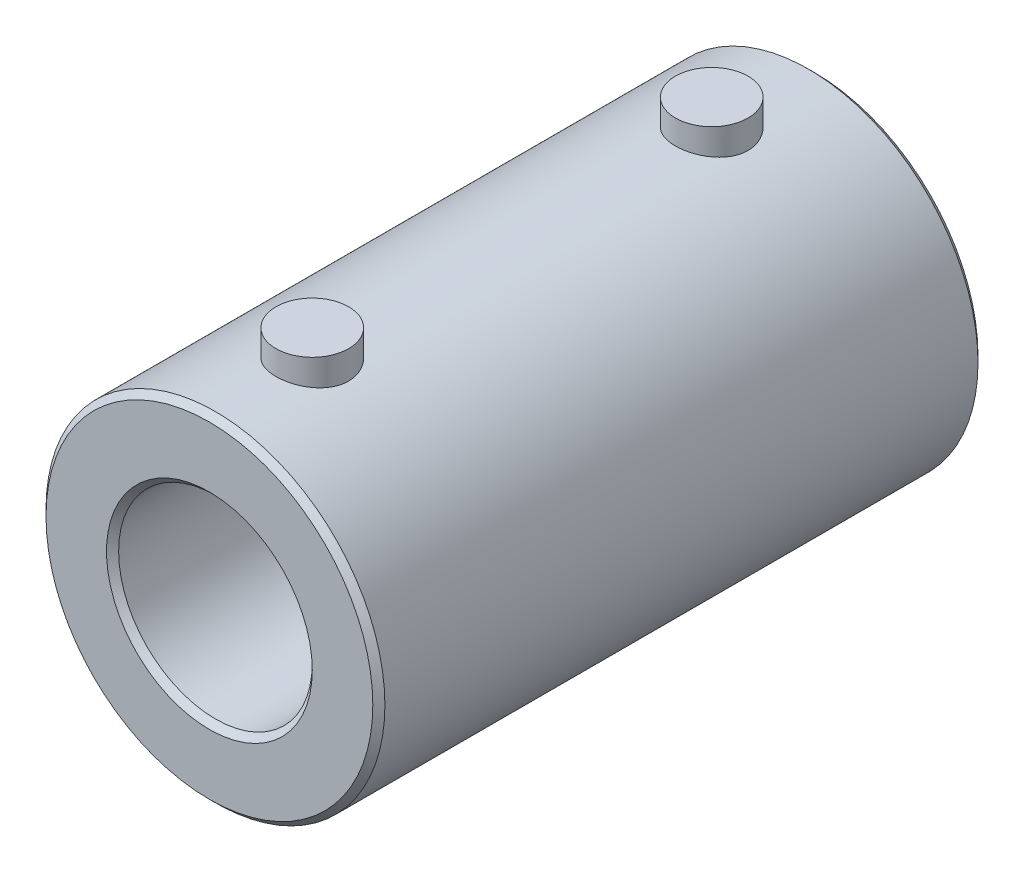
SolidWorks part; units mm, degrees
ref_plane "Front" through (0, 0, 0) normal (0, 0, 1) x (1, 0, 0)
ref_plane "Top" through (0, 0, 0) normal (0, 1, 0) x (1, 0, 0)
ref_plane "Right" through (0, 0, 0) normal (1, 0, 0) x (0, 0, -1)
sketch "Esquisse1" plane through (0, 0, 0) normal (0, 0, 1) x (1, 0, 0)
  circle A0 centre (0, 0) radius 7
  circle A1 centre (0, 0) radius 4
  dimension "D1" = 8
  dimension "D2" = 14
extrude "Boss.-Extru.1" add sketch "Esquisse1" along normal blind 25
chamfer "Chanfrein1" distance 0.25 angle 45 4 edges at (4, 0, 0) (7, 0, 0) (4, 0, 25) (7, 0, 25)
sketch "Esquisse2" plane through (0, 0, 0) normal (0, 1, 0) x (1, 0, 0)
  line L0 (0, -4.25) -> (0, -0.25) construction
  line L1 (7, -0.25) -> (-7, -0.25) construction
  line L2 (7, -12.5) -> (-7, -12.5) construction
  line L3 (7, -24.75) -> (7, -0.25) construction
  line L4 (-7, -0.25) -> (-7, -24.75) construction
  circle A0 centre (0, -4.25) radius 1.5
  circle A1 centre (0, -20.75) radius 1.5
  dimension "D2" = 3
  dimension "D1" = 4
extrude "Boss.-Extru.2" add sketch "Esquisse2" along normal blind 3 from offset 5
